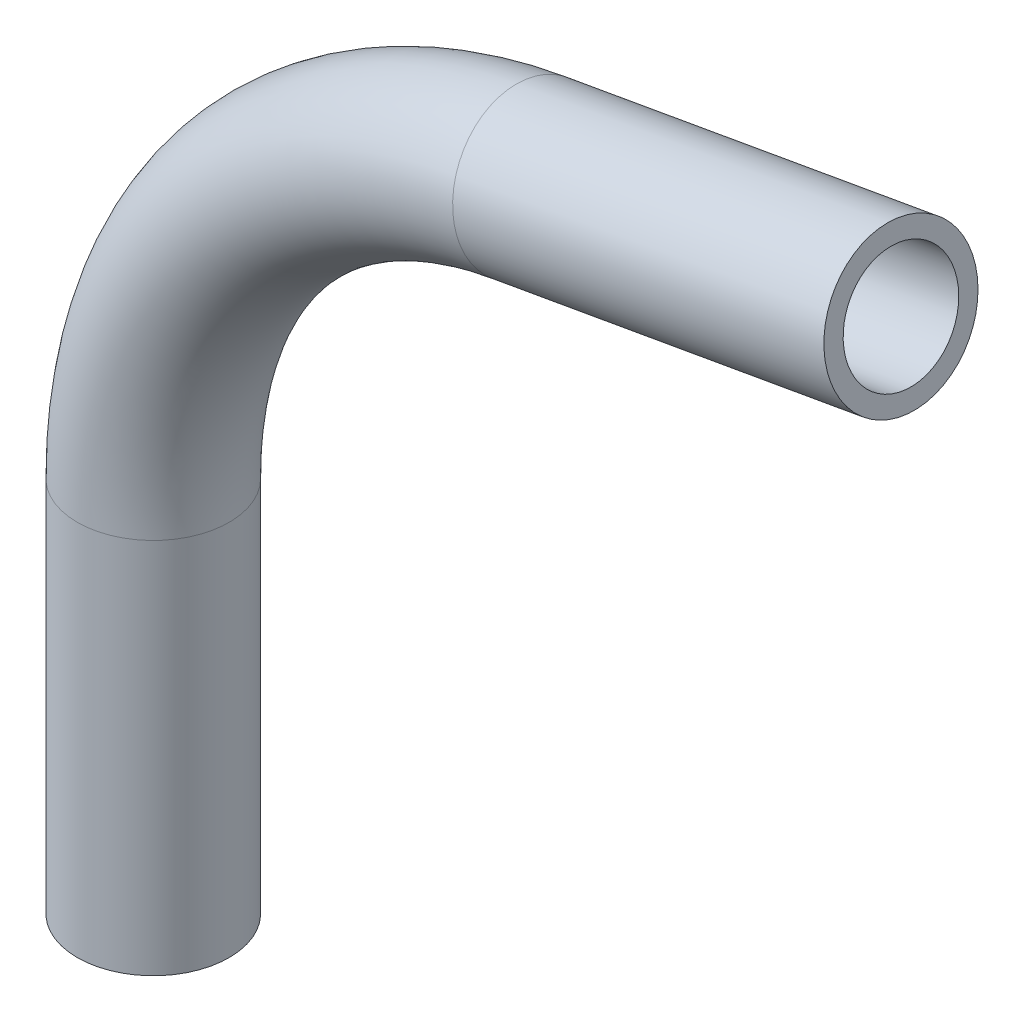
SolidWorks part; units mm, degrees
ref_plane "Front Plane" through (0, 0, 0) normal (0, 0, 1) x (1, 0, 0)
ref_plane "Top Plane" through (0, 0, 0) normal (0, 1, 0) x (1, 0, 0)
ref_plane "Right Plane" through (0, 0, 0) normal (1, 0, 0) x (0, 0, -1)
sketch "Sketch1" plane through (0, 0, 0) normal (0, 0, 1) x (1, 0, 0)
  line L0 (0, 0) -> (0, 19.8616)
  line L1 (19.8324, 43.497) -> (39.3923, 46.9459)
  arc A0 (0, 19.8616) -> (19.8324, 43.497) centre (24, 19.8616) cw
  point P6 (0, 40)
  dimension "D3" = 24
  dimension "D1" = 40
  dimension "D2" = 40
  dimension "D4" = 100
sketch "Sketch2" plane through (0, 0, 0) normal (0, 1, 0) x (1, 0, 0)
  circle A0 centre (0, 0) radius 4
  circle A1 centre (0, 0) radius 3
  dimension "D1" = 6
  dimension "D2" = 8
sweep "Sweep1" add profiles "Sketch2" path "Sketch1"
